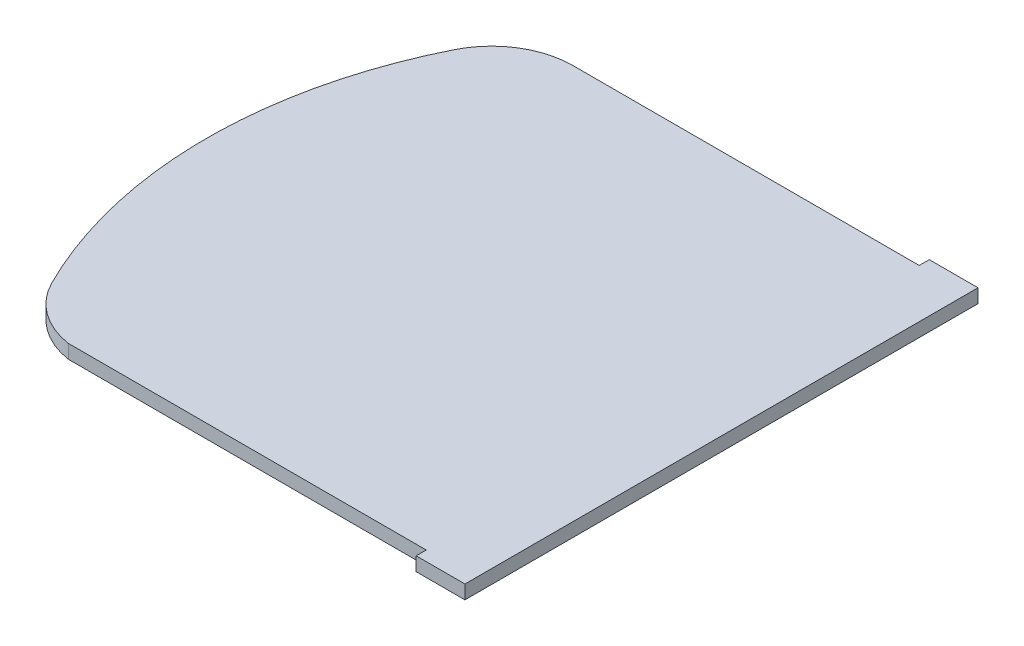
SolidWorks part; units mm, degrees
ref_plane "Front Plane" through (0, 0, 0) normal (0, 0, 1) x (1, 0, 0)
ref_plane "Top Plane" through (0, 0, 0) normal (0, 1, 0) x (1, 0, 0)
ref_plane "Right Plane" through (0, 0, 0) normal (1, 0, 0) x (0, 0, -1)
sketch "Sketch1" plane through (0, 0, 0) normal (0, 1, 0) x (1, 0, 0)
  line L0 (-782.8481, 0) -> (946.4752, 0) construction
  line L1 (0, 242) -> (0, -242)
  line L2 (0, 242) -> (-46, 242)
  line L3 (-46, 242) -> (-46, 232.5)
  line L4 (-46, 232.5) -> (-372.4432, 232.5)
  line L5 (-383.656, -232.5) -> (-46, -232.5)
  line L6 (-46, -232.5) -> (-46, -242)
  line L7 (-46, -242) -> (0, -242)
  arc A0 (-372.4432, 232.5) -> (-441.3777, 189.808) centre (-372.4432, 155.5) ccw
  arc A1 (-441.3777, 189.808) -> (-440.8367, -190.8911) centre (-60, 0) ccw
  arc A2 (-440.8367, -190.8911) -> (-383.656, -232.5) centre (-372, -156.3873) ccw
  dimension "D1" = 426
  dimension "D3" = 77
  dimension "D4" = 77
  dimension "D2" = 60
  dimension "D5" = 46
  dimension "D6" = 46
  dimension "D7" = 372
  dimension "D8" = 465
  dimension "D9" = 484
extrude "Boss-Extrude1" add sketch "Sketch1" along normal mid plane 13
